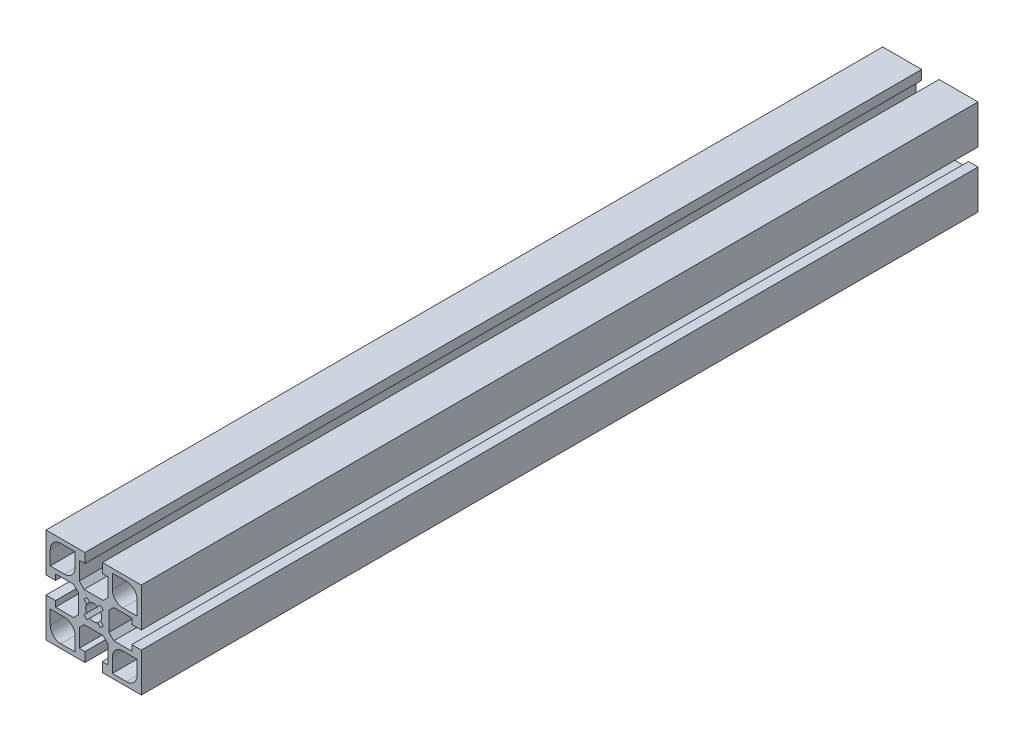
SolidWorks part; units mm, degrees
material "6061 Alloy"
ref_plane "Front Plane" through (0, 0, 0) normal (0, 0, 1) x (1, 0, 0)
ref_plane "Top Plane" through (0, 0, 0) normal (0, 1, 0) x (1, 0, 0)
ref_plane "Right Plane" through (0, 0, 0) normal (1, 0, 0) x (0, 0, -1)
sketch "Sketch1" plane through (0, 0, 0) normal (0, 0, 1) x (1, 0, 0)
  line L4 (-20.5, 8.8) -> (-20.5, 15.5)
  line L5 (-13.8, 8.8) -> (-20.5, 8.8)
  line L6 (-8.8, 20.5) -> (-8.8, 13.8)
  line L7 (-15.5, 20.5) -> (-8.8, 20.5)
  line L12 (20.5, 8.8) -> (13.8, 8.8)
  line L13 (20.5, 15.5) -> (20.5, 8.8)
  line L14 (8.8, 20.5) -> (15.5, 20.5)
  line L15 (8.8, 13.8) -> (8.8, 20.5)
  line L20 (15.5, -20.5) -> (8.8, -20.5)
  line L21 (20.5, -8.8) -> (20.5, -15.5)
  line L22 (13.8, -8.8) -> (20.5, -8.8)
  line L23 (8.8, -20.5) -> (8.8, -13.8)
  line L28 (-8.8, -20.5) -> (-15.5, -20.5)
  line L29 (-8.8, -13.8) -> (-8.8, -20.5)
  line L30 (-20.5, -8.8) -> (-13.8, -8.8)
  line L31 (-20.5, -15.5) -> (-20.5, -8.8)
  line L88 (-18, -6.8) -> (-18, -4.1)
  line L89 (-18, -4.1) -> (-22.5, -4.1)
  line L90 (-22.5, -4.1) -> (-22.5, -22.5)
  line L91 (-22.5, -22.5) -> (-4.1, -22.5)
  line L92 (-4.1, -22.5) -> (-4.1, -18)
  line L93 (-4.1, -18) -> (-6.8, -18)
  line L94 (-6.8, -18) -> (-6.8, -9.5)
  line L95 (-6.8, -9.5) -> (-4.5, -7.2)
  line L96 (-4.5, -7.2) -> (4.5, -7.2)
  line L97 (4.5, -7.2) -> (6.8, -9.5)
  line L98 (6.8, -9.5) -> (6.8, -18)
  line L99 (6.8, -18) -> (4.1, -18)
  line L100 (4.1, -18) -> (4.1, -22.5)
  line L101 (4.1, -22.5) -> (22.5, -22.5)
  line L102 (22.5, -22.5) -> (22.5, -4.1)
  line L103 (22.5, -4.1) -> (18, -4.1)
  line L104 (18, -4.1) -> (18, -6.8)
  line L105 (18, -6.8) -> (9.5, -6.8)
  line L106 (9.5, -6.8) -> (7.2, -4.5)
  line L107 (7.2, -4.5) -> (7.2, 4.5)
  line L108 (7.2, 4.5) -> (9.5, 6.8)
  line L109 (9.5, 6.8) -> (18, 6.8)
  line L110 (18, 6.8) -> (18, 4.1)
  line L111 (18, 4.1) -> (22.5, 4.1)
  line L112 (22.5, 4.1) -> (22.5, 22.5)
  line L113 (22.5, 22.5) -> (4.1, 22.5)
  line L114 (4.1, 22.5) -> (4.1, 18)
  line L115 (4.1, 18) -> (6.8, 18)
  line L116 (6.8, 18) -> (6.8, 9.5)
  line L117 (6.8, 9.5) -> (4.5, 7.2)
  line L118 (4.5, 7.2) -> (-4.5, 7.2)
  line L119 (-4.5, 7.2) -> (-6.8, 9.5)
  line L120 (-6.8, 9.5) -> (-6.8, 18)
  line L121 (-6.8, 18) -> (-4.1, 18)
  line L122 (-4.1, 18) -> (-4.1, 22.5)
  line L123 (-4.1, 22.5) -> (-22.5, 22.5)
  line L124 (-22.5, 22.5) -> (-22.5, 4.1)
  line L125 (-22.5, 4.1) -> (-18, 4.1)
  line L126 (-18, 4.1) -> (-18, 6.8)
  line L127 (-18, 6.8) -> (-9.5, 6.8)
  line L128 (-9.5, 6.8) -> (-7.2, 4.5)
  line L129 (-7.2, 4.5) -> (-7.2, -4.5)
  line L130 (-7.2, -4.5) -> (-9.5, -6.8)
  line L131 (-9.5, -6.8) -> (-18, -6.8)
  line L132 (-3.2627, 1.8485) -> (-4.5962, 3.182)
  line L133 (-4.5962, -3.182) -> (-3.2627, -1.8485)
  line L134 (-3.182, -4.5962) -> (-4.5962, -3.182)
  line L135 (-1.8485, -3.2627) -> (-3.182, -4.5962)
  line L136 (3.182, -4.5962) -> (1.8485, -3.2627)
  line L137 (4.5962, -3.182) -> (3.182, -4.5962)
  line L138 (3.2627, -1.8485) -> (4.5962, -3.182)
  line L139 (4.5962, 3.182) -> (3.2627, 1.8485)
  line L140 (3.182, 4.5962) -> (4.5962, 3.182)
  line L141 (1.8485, 3.2627) -> (3.182, 4.5962)
  line L142 (-3.182, 4.5962) -> (-1.8485, 3.2627)
  line L143 (-4.5962, 3.182) -> (-3.182, 4.5962)
  arc A2 (-13.8, 8.8) -> (-8.8, 13.8) centre (-13.8, 13.8) ccw
  arc A3 (-15.5, 20.5) -> (-20.5, 15.5) centre (-15.5, 15.5) ccw
  arc A6 (8.8, 13.8) -> (13.8, 8.8) centre (13.8, 13.8) ccw
  arc A7 (20.5, 15.5) -> (15.5, 20.5) centre (15.5, 15.5) ccw
  arc A10 (15.5, -20.5) -> (20.5, -15.5) centre (15.5, -15.5) ccw
  arc A11 (13.8, -8.8) -> (8.8, -13.8) centre (13.8, -13.8) ccw
  arc A14 (-20.5, -15.5) -> (-15.5, -20.5) centre (-15.5, -15.5) ccw
  arc A15 (-8.8, -13.8) -> (-13.8, -8.8) centre (-13.8, -13.8) ccw
  arc A20 (-3.2627, 1.8485) -> (-3.2627, -1.8485) centre (0, 0) ccw
  arc A21 (-1.8485, -3.2627) -> (1.8485, -3.2627) centre (0, 0) ccw
  arc A22 (3.2627, -1.8485) -> (3.2627, 1.8485) centre (0, 0) ccw
  arc A23 (1.8485, 3.2627) -> (-1.8485, 3.2627) centre (0, 0) ccw
extrude "Boss-Extrude1" add sketch "Sketch1" along normal blind 395
